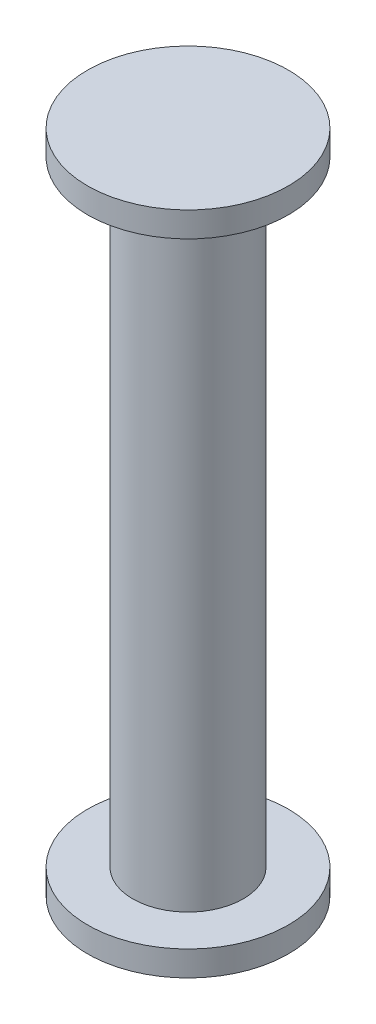
SolidWorks part; units mm, degrees
ref_plane "Front Plane" through (0, 0, 0) normal (0, 0, 1) x (1, 0, 0)
ref_plane "Top Plane" through (0, 0, 0) normal (0, 1, 0) x (1, 0, 0)
ref_plane "Right Plane" through (0, 0, 0) normal (1, 0, 0) x (0, 0, -1)
sketch "Sketch1" plane through (0, 0, 0) normal (0, 1, 0) x (1, 0, 0)
  circle A0 centre (0, 0) radius 2.2
  dimension "D1" = 4.4
extrude "Boss-Extrude1" add sketch "Sketch1" along normal blind 24.5 contours A0
sketch "Sketch2" plane through (0, 24.5, 0) normal (0, 1, 0) x (1, 0, 0)
  circle A0 centre (0, 0) radius 4
  dimension "D1" = 8
extrude "Boss-Extrude2" add sketch "Sketch2" along normal blind 1 contours A0
sketch "Sketch3" plane through (0, 0, 0) normal (0, -1, 0) x (1, 0, 0)
  circle A0 centre (0, 0) radius 4
  dimension "D1" = 8
extrude "Boss-Extrude3" add sketch "Sketch3" along normal blind 1
